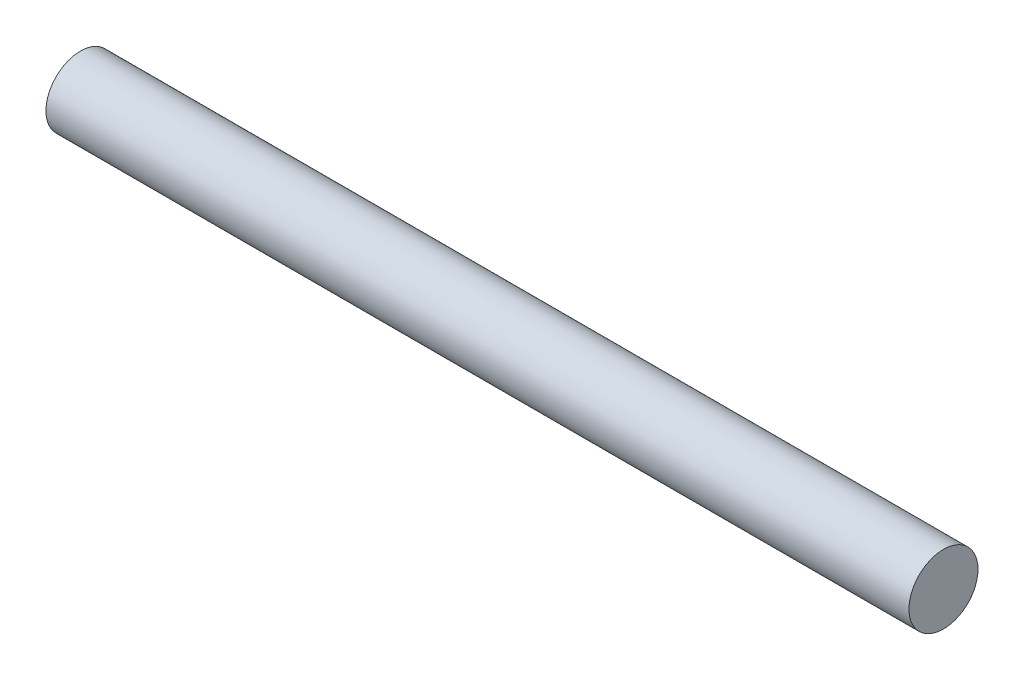
SolidWorks part; units mm, degrees
ref_plane "Front Plane" through (0, 0, 0) normal (0, 0, 1) x (1, 0, 0)
ref_plane "Top Plane" through (0, 0, 0) normal (0, 1, 0) x (1, 0, 0)
ref_plane "Right Plane" through (0, 0, 0) normal (1, 0, 0) x (0, 0, -1)
sketch "Sketch1" plane through (0, 0, 0) normal (1, 0, 0) x (0, 0, -1)
  circle A0 centre (-11.905, 2.3657) radius 0.8
extrude "Boss-Extrude1" add sketch "Sketch1" along normal blind 20
